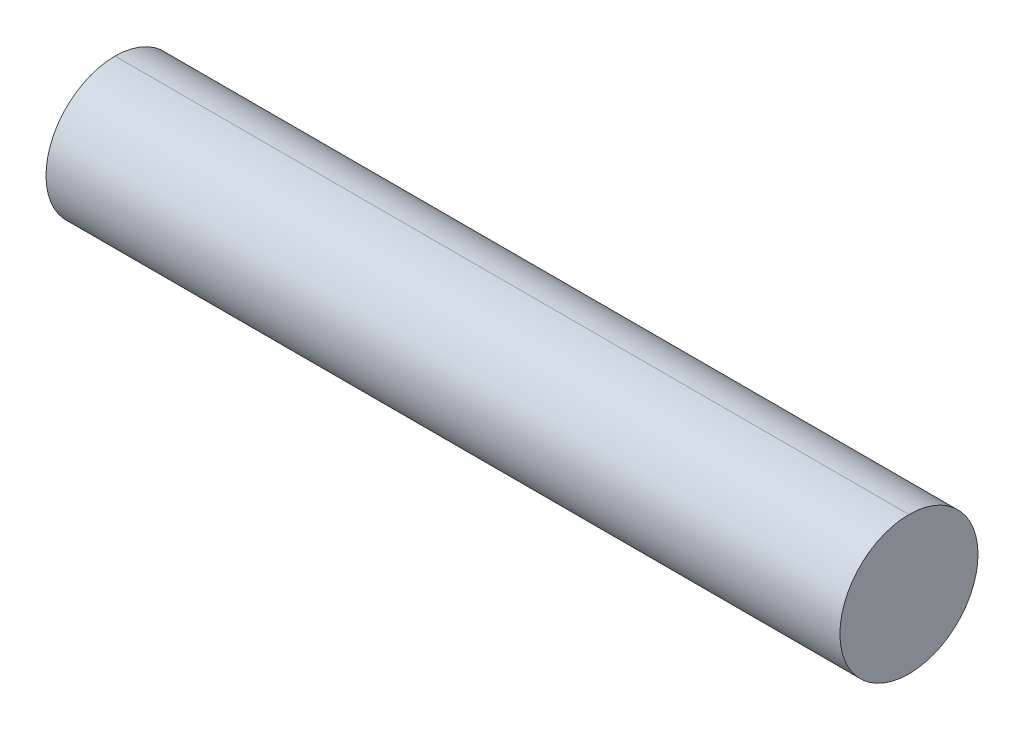
SolidWorks part; units mm, degrees
ref_plane "Front Plane" through (0, 0, 0) normal (0, 0, 1) x (1, 0, 0)
ref_plane "Top Plane" through (0, 0, 0) normal (0, 1, 0) x (1, 0, 0)
ref_plane "Right Plane" through (0, 0, 0) normal (1, 0, 0) x (0, 0, -1)
sketch "Sketch1" plane through (0, 0, 0) normal (1, 0, 0) x (0, 0, -1)
  circle A0 centre (0, 0) radius 12.7
  dimension "D1" = 25.4
extrude "Boss-Extrude1" add sketch "Sketch1" along normal blind 146.05
split line "Split Line1"
